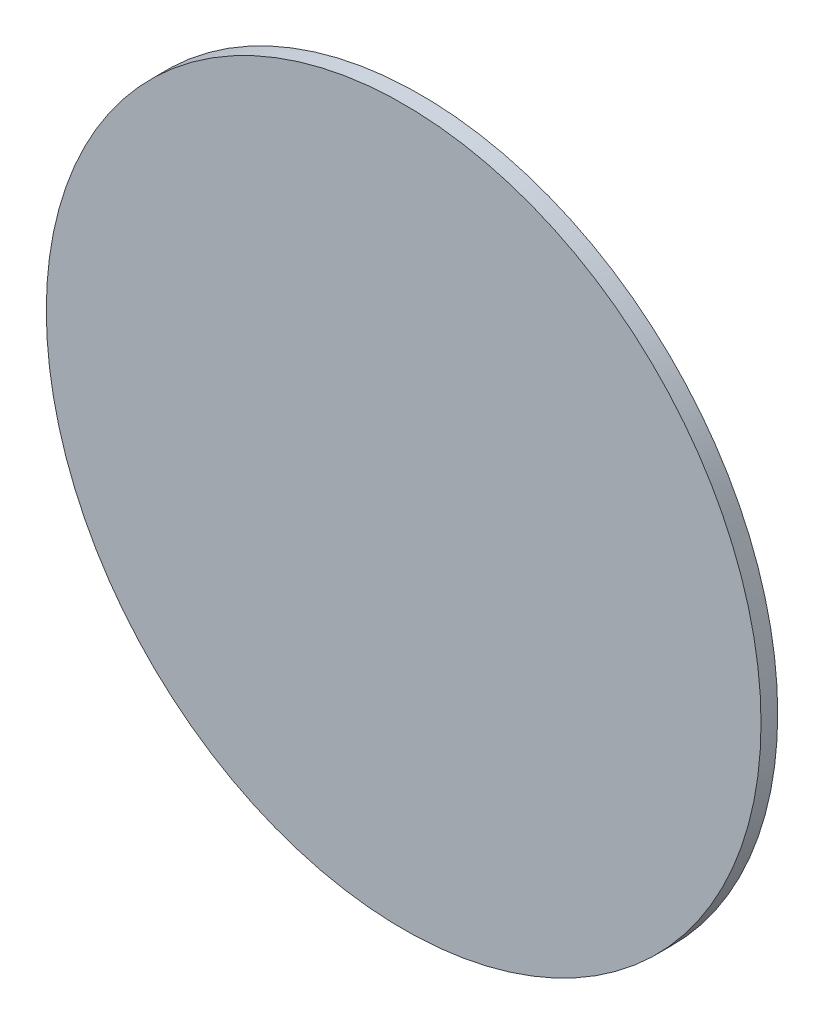
SolidWorks part; units mm, degrees
ref_plane "Front Plane" through (0, 0, 0) normal (0, 0, 1) x (1, 0, 0)
ref_plane "Top Plane" through (0, 0, 0) normal (0, 1, 0) x (1, 0, 0)
ref_plane "Right Plane" through (0, 0, 0) normal (1, 0, 0) x (0, 0, -1)
sketch "Sketch1" plane through (0, 0, 0) normal (0, 0, 1) x (1, 0, 0)
  circle A0 centre (0, 0) radius 114.3
  dimension "D1" = 228.6
extrude "Platform" add sketch "Sketch1" along normal blind 5.334
